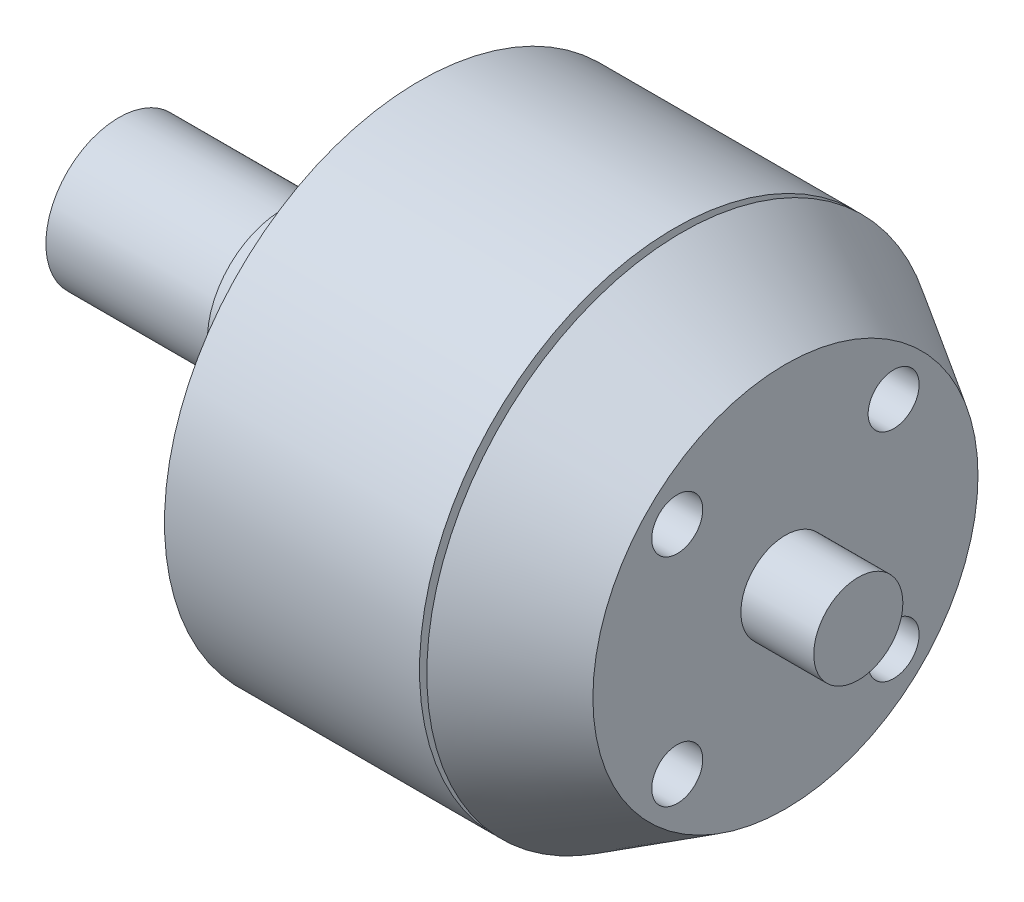
SolidWorks part; units mm, degrees
material "Alloy Steel"
ref_plane "Front Plane" through (0, 0, 0) normal (0, 0, 1) x (1, 0, 0)
ref_plane "Top Plane" through (0, 0, 0) normal (0, 1, 0) x (1, 0, 0)
ref_plane "Right Plane" through (0, 0, 0) normal (1, 0, 0) x (0, 0, -1)
sketch "Sketch2" plane through (0, 0, 0) normal (0, 1, 0) x (1, 0, 0)
  line L1 (-2.3455, 2.0677) -> (-2.3455, 3)
  line L3 (-1.8455, 3) -> (-0.0895, 7)
  line L5 (-0.0895, 7) -> (6.9105, 7)
  line L6 (6.9105, 7) -> (6.9105, 5.2854)
  line L7 (6.9105, 5.2854) -> (7.1105, 5.2854)
  line L8 (7.1105, 5.2854) -> (7.1105, 7)
  line L9 (7.1105, 7) -> (9.9545, 5.2854)
  line L10 (9.9545, 5.2854) -> (9.9545, 1.2231)
  line L11 (9.9545, 1.2231) -> (11.9545, 1.2231)
  line L12 (11.9545, 1.2231) -> (11.9545, 0)
  line L13 (11.9545, 0) -> (-8.3455, 0)
  line L14 (-8.3455, 0) -> (-8.3455, 2)
  line L15 (-8.3455, 2) -> (-3.8455, 2)
  line L16 (-3.8455, 2) -> (-3.8455, 2.0677)
  line L17 (-3.8455, 2.0677) -> (-2.3455, 2.0677)
  line L18 (-2.3455, 3) -> (-1.8455, 3)
revolve "Revolve1" add sketch "Sketch2" angle 360 about L13
sketch "Sketch3" plane through (9.9545, 0, 0) normal (1, 0, 0) x (0, 0, -1)
  line L1 (-2.9698, 2.9698) -> (2.9698, 2.9698) construction
  line L2 (-2.9698, 2.9698) -> (-2.9698, -2.9698) construction
  line L3 (-2.9698, -2.9698) -> (2.9698, -2.9698) construction
  line L4 (2.9698, 2.9698) -> (2.9698, -2.9698) construction
  circle A0 centre (0, 0) radius 4.2 construction
  circle A1 centre (2.9698, 2.9698) radius 0.7
  circle A2 centre (2.9698, -2.9698) radius 0.7
  circle A3 centre (-2.9698, -2.9698) radius 0.7
  circle A4 centre (-2.9698, 2.9698) radius 0.7
extrude "Cut-Extrude1" cut sketch "Sketch3" against normal blind 2
